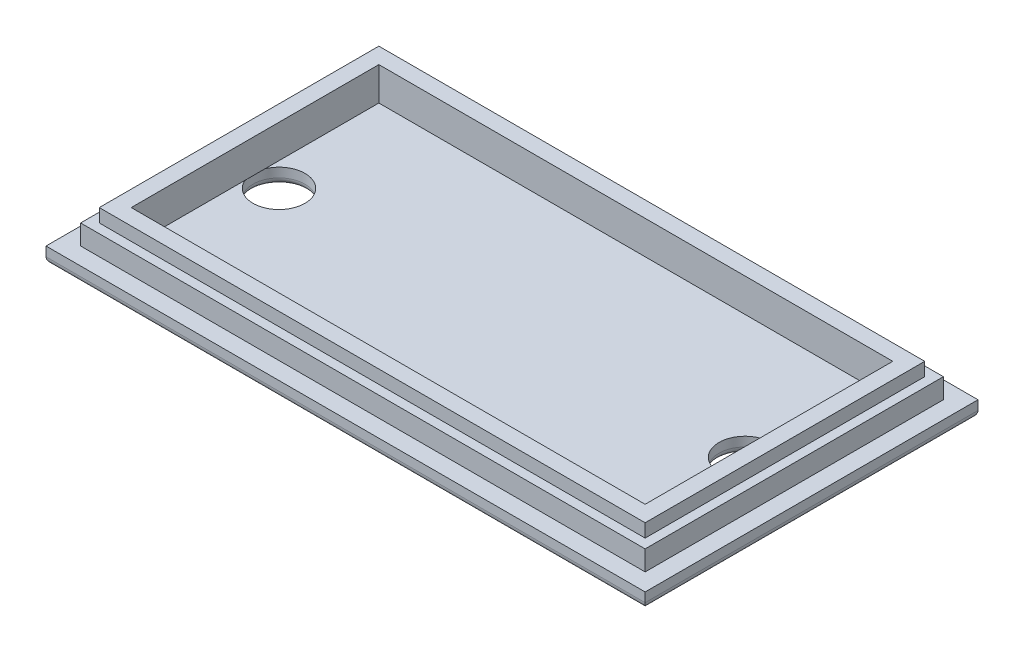
SolidWorks part; units mm, degrees
ref_plane "Front Plane" through (0, 0, 0) normal (0, 0, 1) x (1, 0, 0)
ref_plane "Top Plane" through (0, 0, 0) normal (0, 1, 0) x (1, 0, 0)
ref_plane "Right Plane" through (0, 0, 0) normal (1, 0, 0) x (0, 0, -1)
sketch "Sketch1" plane through (0, 0, 0) normal (0, 0, 1) x (1, 0, 0)
  line L1 (0, 0) -> (45, 0)
  line L2 (0, 0) -> (0, 1.2)
  line L3 (0, 1.2) -> (45, 1.2)
  line L4 (45, 0) -> (45, 1.2)
  dimension "D1" = 1.2
  dimension "D2" = 45
extrude "Boss-Extrude1" add sketch "Sketch1" against normal blind 25
sketch "Sketch2" plane through (0, 1.2, 0) normal (0, 1, 0) x (1, 0, 0)
  line L0 (0, 25) -> (1.3, 25) construction
  line L1 (45, 25) -> (0, 25) construction
  line L2 (1.3, 25) -> (1.3, 23.7) construction
  line L3 (1.3, 23.7) -> (0, 23.7) construction
  line L4 (0, 25) -> (0, 0) construction
  line L5 (45, 0) -> (45, 1.3) construction
  line L6 (45, 25) -> (45, 0) construction
  line L7 (45, 1.3) -> (43.7, 1.3) construction
  line L9 (1.3, 23.7) -> (43.7, 23.7)
  line L10 (1.3, 23.7) -> (1.3, 1.3)
  line L11 (1.3, 1.3) -> (43.7, 1.3)
  line L12 (43.7, 23.7) -> (43.7, 1.3)
  dimension "D1" = 1.3
  dimension "D2" = 1.3
  dimension "D3" = 1.3
extrude "Extrude-Thin1" add sketch "Sketch2" along normal blind 1.5 thin contours L9 L12 L11 L10
sketch "Sketch3" plane through (0, 0, 0) normal (0, -1, 0) x (1, 0, 0)
  line L0 (0, -12.5) -> (5, -12.5)
  line L1 (0, -25) -> (0, 0) construction
  line L2 (45, -12.5) -> (40, -12.5)
  line L3 (45, -25) -> (45, 0) construction
hole_wizard "#6 (0.204) Diameter Hole1" positions "Sketch4" profile "Sketch5" hole size "#6" standard "ANSI Inch" end condition through all
sketch "Sketch4" plane through (0, 0, 0) normal (0, -1, 0) x (-1, 0, 0)
  point P0 (-5, 12.5)
  point P3 (-40, 12.5)
sketch "Sketch5" plane through (5, 0, -12.5) normal (1, 0, 0) x (0, 0, -1)
  line L0 (0, 0) -> (0, 2.7)
  line L1 (0, 2.7) -> (1.95, 2.7)
  line L2 (1.95, 2.7) -> (1.95, 0)
  line L5 (1.95, 0) -> (0, 0)
  line L11 (0, -6.35) -> (0, 107.95) construction
  dimension "Thru Hole Dia." = 3.9
  dimension "Thru Hole Depth" = 2.7
sketch "Sketch6" plane through (0, 1.2, 0) normal (0, 1, 0) x (1, 0, 0)
  line L0 (0, 25) -> (2, 25) construction
  line L1 (45, 25) -> (0, 25) construction
  line L2 (2, 25) -> (2, 23) construction
  line L3 (45, 0) -> (45, 2)
  line L4 (45, 25) -> (45, 0) construction
  line L5 (45, 2) -> (43, 2)
  line L7 (2, 23) -> (43, 23)
  line L8 (2, 23) -> (2, 2)
  line L9 (2, 2) -> (43, 2)
  line L10 (43, 23) -> (43, 2)
  dimension "D1" = 2
  dimension "D2" = 2
  dimension "D3" = 2
extrude "Extrude-Thin2" add sketch "Sketch6" along normal blind 2.5 thin contours L9 L8 L7 L10
fillet "Fillet1" radius 0.5 6 edges at (45, 0, -12.5) (22.5, 0, -25) (0, 0, -12.5) (22.5, 0, 0) (40, 0, -14.45) (5, 0, -14.45)
